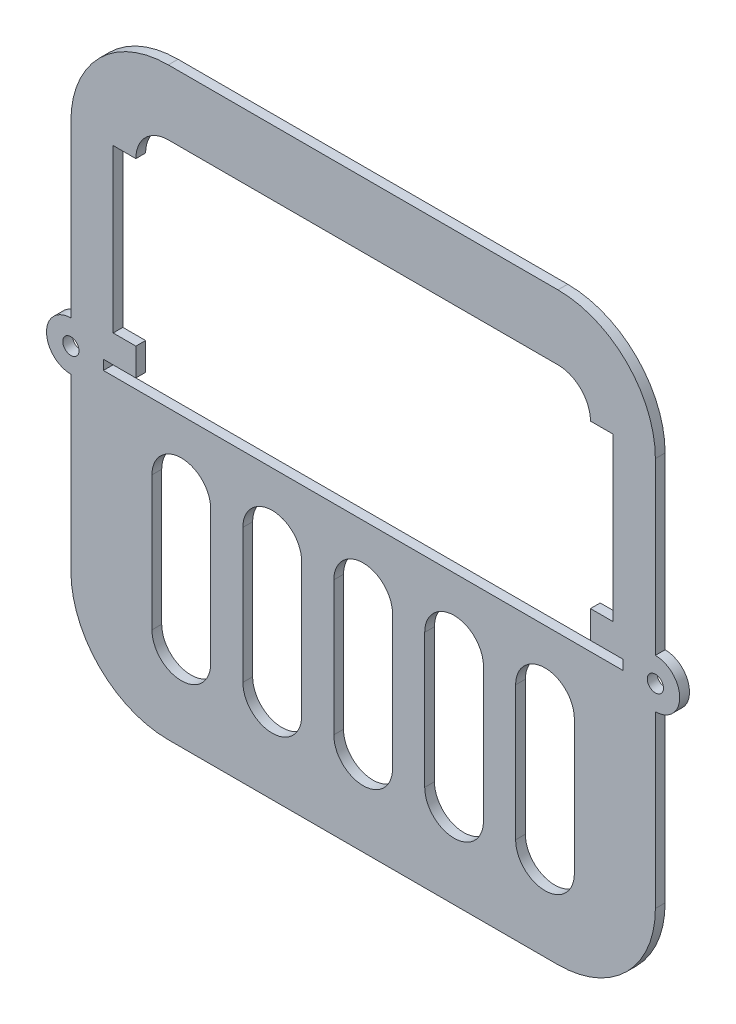
SolidWorks part; units mm, degrees
material "Teak"
ref_plane "Front Plane" through (0, 0, 0) normal (0, 0, 1) x (1, 0, 0)
ref_plane "Top Plane" through (0, 0, 0) normal (0, 1, 0) x (1, 0, 0)
ref_plane "Right Plane" through (0, 0, 0) normal (1, 0, 0) x (0, 0, -1)
sketch "Sketch1" plane through (0, 0, 0) normal (0, 0, 1) x (1, 0, 0)
  line L33 (167.7762, -174.9603) -> (287.7762, -174.9603)
  line L38 (317.7762, -144.9603) -> (317.7762, -92.4603)
  line L41 (226.2847, -14.9603) -> (167.7847, -14.9603)
  line L44 (229.2847, -14.9603) -> (226.2847, -14.9603)
  line L47 (287.7847, -14.9603) -> (229.2847, -14.9603)
  line L48 (304.7847, -24.9603) -> (297.7847, -24.9603)
  line L49 (304.7847, -74.9603) -> (304.7847, -24.9603)
  line L50 (297.7847, -74.9603) -> (304.7847, -74.9603)
  line L51 (297.7847, -83.4603) -> (297.7847, -74.9603)
  line L52 (307.7847, -83.4603) -> (297.7847, -83.4603)
  line L53 (307.7847, -86.4603) -> (307.7847, -83.4603)
  line L54 (297.7847, -86.4603) -> (307.7847, -86.4603)
  line L59 (157.7847, -74.9603) -> (157.7847, -83.4603)
  line L60 (150.7847, -74.9603) -> (157.7847, -74.9603)
  line L61 (150.7847, -24.9603) -> (150.7847, -74.9603)
  line L62 (157.7847, -24.9603) -> (150.7847, -24.9603)
  line L63 (287.7762, 5.0397) -> (167.7762, 5.0397)
  line L64 (137.7762, -24.9603) -> (137.7762, -77.4603)
  line L69 (227.7847, -97.5637) -> (227.7847, -97.7828) construction
  line L70 (147.7847, -86.4603) -> (147.7847, -83.4603)
  line L71 (157.7847, -86.4603) -> (147.7847, -86.4603)
  line L72 (147.7847, -83.4603) -> (157.7847, -83.4603)
  line L75 (157.7847, -86.4603) -> (297.7847, -86.4603)
  line L96 (246.7436, -106.8239) -> (246.7436, -148.1639)
  line L97 (137.7762, -92.4603) -> (137.7762, -144.9603)
  line L98 (317.7762, -77.4603) -> (317.7762, -24.9603)
  line L99 (236.8258, -106.8239) -> (236.8258, -148.1639)
  line L100 (218.7436, -106.8239) -> (218.7436, -148.1639)
  line L101 (264.8258, -106.8239) -> (264.8258, -148.1639)
  line L102 (274.7436, -106.8239) -> (274.7436, -148.1639)
  line L103 (292.8258, -106.8239) -> (292.8258, -148.1639)
  line L104 (190.7436, -106.8239) -> (190.7436, -148.1639)
  line L105 (208.8258, -106.8239) -> (208.8258, -148.1639)
  line L106 (162.7436, -106.8239) -> (162.7436, -148.1639)
  line L107 (180.8258, -106.8239) -> (180.8258, -148.1639)
  arc A22 (167.7847, -14.9603) -> (157.7847, -24.9603) centre (167.7847, -24.9603) ccw
  arc A23 (297.7847, -24.9603) -> (287.7847, -14.9603) centre (287.7847, -24.9603) ccw
  arc A26 (137.7762, -144.9603) -> (167.7762, -174.9603) centre (167.7762, -144.9603) ccw
  arc A27 (287.7762, -174.9603) -> (317.7762, -144.9603) centre (287.7762, -144.9603) ccw
  arc A28 (317.7762, -24.9603) -> (287.7762, 5.0397) centre (287.7762, -24.9603) ccw
  arc A29 (167.7762, 5.0397) -> (137.7762, -24.9603) centre (167.7762, -24.9603) ccw
  circle A50 centre (317.7762, -84.9603) radius 2.5
  arc A51 (317.7762, -92.4603) -> (317.7762, -77.4603) centre (317.7762, -84.9603) ccw
  circle A52 centre (137.7762, -84.9603) radius 2.5
  arc A53 (137.7762, -77.4603) -> (137.7762, -92.4603) centre (137.7762, -84.9603) ccw
  arc A54 (236.8258, -106.8239) -> (218.7436, -106.8239) centre (227.7847, -106.8239) ccw
  arc A55 (218.7436, -148.1639) -> (236.8258, -148.1639) centre (227.7847, -148.1639) ccw
  arc A56 (264.8258, -106.8239) -> (246.7436, -106.8239) centre (255.7847, -106.8239) ccw
  arc A57 (246.7436, -148.1639) -> (264.8258, -148.1639) centre (255.7847, -148.1639) ccw
  arc A58 (292.8258, -106.8239) -> (274.7436, -106.8239) centre (283.7847, -106.8239) ccw
  arc A59 (274.7436, -148.1639) -> (292.8258, -148.1639) centre (283.7847, -148.1639) ccw
  arc A60 (208.8258, -106.8239) -> (190.7436, -106.8239) centre (199.7847, -106.8239) ccw
  arc A61 (190.7436, -148.1639) -> (208.8258, -148.1639) centre (199.7847, -148.1639) ccw
  arc A62 (180.8258, -106.8239) -> (162.7436, -106.8239) centre (171.7847, -106.8239) ccw
  arc A63 (162.7436, -148.1639) -> (180.8258, -148.1639) centre (171.7847, -148.1639) ccw
  dimension "D1" = 15
  dimension "D2" = 5
  dimension "D4" = 15
  dimension "D5" = 5
  dimension "D6" = 3
  dimension "D7" = 3
extrude "Boss-Extrude1" add sketch "Sketch1" along normal blind 3
